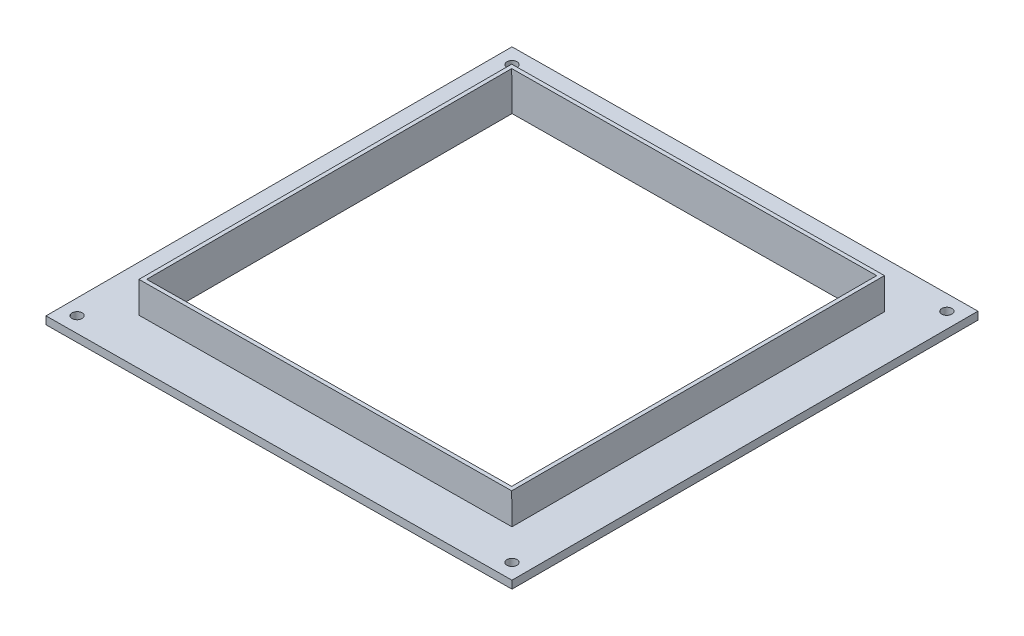
SolidWorks part; units mm, degrees
ref_plane "Front Plane" through (0, 0, 0) normal (0, 0, 1) x (1, 0, 0)
ref_plane "Top Plane" through (0, 0, 0) normal (0, 1, 0) x (1, 0, 0)
ref_plane "Right Plane" through (0, 0, 0) normal (1, 0, 0) x (0, 0, -1)
sketch "Sketch3" plane through (0, 0, 0) normal (0, 1, 0) x (1, 0, 0)
  line L0 (0, 0) -> (300, 300)
  line L1 (0, 0) -> (300, 0)
  line L2 (0, 0) -> (0, 300)
  line L3 (0, 300) -> (300, 300)
  line L4 (300, 0) -> (300, 300)
  line L5 (300, 0) -> (0, 300)
  dimension "D1" = 300
  dimension "D2" = 300
extrude "Boss-Extrude1" add sketch "Sketch3" along normal blind 5 contours L5 L4 L0 | L1 L5 L0 | L0 L5 L2 | L5 L0 L3
sketch "Sketch4" plane through (0, 5, 0) normal (0, 1, 0) x (1, 0, 0)
  line L0 (0, 0) -> (300, 300)
  line L1 (0, 300) -> (300, 0)
  line L5 (30, 30) -> (270, 30)
  line L6 (30, 30) -> (30, 270)
  line L7 (30, 270) -> (270, 270)
  line L8 (270, 30) -> (270, 270)
  line L9 (30, 30) -> (270, 270) construction
  line L10 (30, 270) -> (270, 30) construction
  line L11 (34.75, 34.75) -> (265.25, 34.75)
  line L12 (34.75, 34.75) -> (34.75, 265.25)
  line L13 (34.75, 265.25) -> (265.25, 265.25)
  line L14 (265.25, 34.75) -> (265.25, 265.25)
  line L15 (34.75, 34.75) -> (265.25, 265.25) construction
  line L16 (34.75, 265.25) -> (265.25, 34.75) construction
  point P8 (150, 150)
  point P12 (150, 150)
  dimension "D1" = 240
  dimension "D2" = 240
  dimension "D3" = 230.5
  dimension "D4" = 230.5
extrude "Boss-Extrude2" add sketch "Sketch4" along normal blind 20 contours L12 L13 L14 L11 | L6 L7 L8 L5
sketch "Sketch6" plane through (0, 5, 0) normal (0, 1, 0) x (1, 0, 0)
  line L0 (0, 0) -> (10, 0)
  line L1 (0, 0) -> (300, 0) construction
  line L2 (10, 0) -> (10, 10)
  line L3 (10, 10) -> (290, 10)
  line L4 (290, 10) -> (290, 290)
  line L5 (290, 290) -> (10, 290)
  circle A0 centre (10, 10) radius 3.25
  circle A1 centre (290, 10) radius 3.25
  circle A2 centre (290, 290) radius 3.25
  circle A3 centre (10, 290) radius 3.25
  dimension "D1" = 6.5
  dimension "D3" = 6.5
  dimension "D5" = 6.5
  dimension "D6" = 6.5
  dimension "D2" = 280
  dimension "D4" = 280
extrude "Cut-Extrude1" cut sketch "Sketch6" against normal blind 20
sketch "Sketch7" plane through (0, 25, 0) normal (0, 1, 0) x (1, 0, 0)
  line L2 (30, 30) -> (270, 30)
  line L3 (30, 30) -> (30, 270)
  line L4 (30, 270) -> (270, 270)
  line L5 (270, 30) -> (270, 270)
extrude "Cut-Extrude2" cut sketch "Sketch7" against normal blind 20
sketch "Sketch8" plane through (0, 5, 0) normal (0, 1, 0) x (1, 0, 0)
  line L0 (30, 30) -> (270, 30)
  line L1 (0, 0) -> (32.5, 0)
  line L2 (0, 0) -> (300, 0) construction
  line L3 (32.5, 0) -> (32.5, 32.5)
  line L4 (270, 30) -> (270, 270)
  line L5 (32.5, 32.5) -> (267.5, 32.5)
  line L6 (32.5, 32.5) -> (32.5, 267.5)
  line L7 (32.5, 267.5) -> (267.5, 267.5)
  line L8 (267.5, 32.5) -> (267.5, 267.5)
  line L9 (30, 270) -> (270, 270)
  line L10 (30, 30) -> (30, 270)
  dimension "D1" = 235
  dimension "D2" = 235
  dimension "D4" = 240
  dimension "D5" = 240
  dimension "D3" = 2.5
extrude "Boss-Extrude3" add sketch "Sketch8" along normal blind 20
sketch "Sketch9" plane through (0, 5, 0) normal (0, 1, 0) x (1, 0, 0)
  line L1 (32.5, 32.5) -> (267.5, 32.5)
  line L2 (32.5, 32.5) -> (32.5, 267.5)
  line L3 (32.5, 267.5) -> (267.5, 267.5)
  line L4 (267.5, 32.5) -> (267.5, 267.5)
extrude "Cut-Extrude3" cut sketch "Sketch9" against normal blind 20
move or copy body "Body-Move/Copy1" bodies to move or copy 106 copy no rotation origin (150, 12.5, 0) rotation axis (0, 0, -1) rotation angle 89.5
move or copy body "Body-Move/Copy2" bodies to move or copy 107 copy no rotation origin (149.8691, 12.4127, 0) rotation axis (0, 0, 1) rotation angle 90
ref_plane "Plane1" through (0.0983, -11.2635, 0) normal (0.0087, -1, 0) x (-1, -0.0087, 0)
